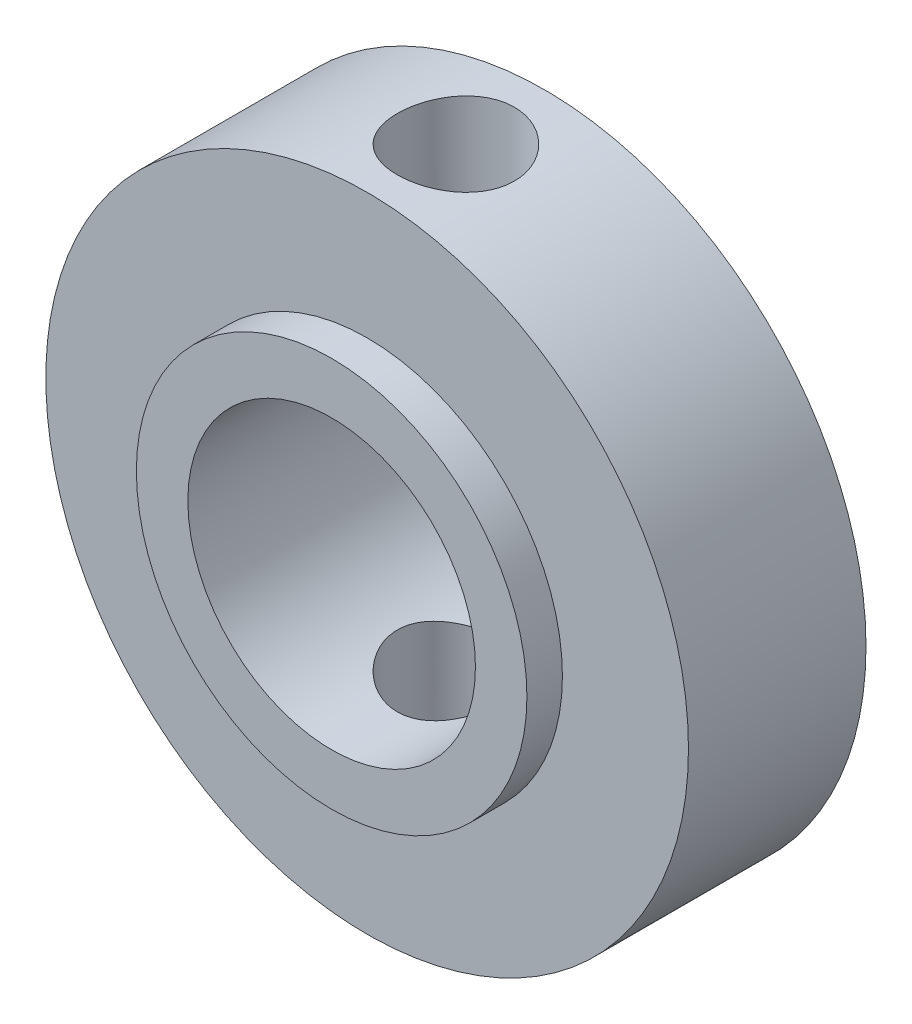
SolidWorks part; units mm, degrees
ref_plane "Plan de face" through (0, 0, 0) normal (0, 0, 1) x (1, 0, 0)
ref_plane "Plan de dessus" through (0, 0, 0) normal (0, 1, 0) x (1, 0, 0)
ref_plane "Plan de droite" through (0, 0, 0) normal (1, 0, 0) x (0, 0, -1)
sketch "Esquisse1" plane through (0, 0, 0) normal (0, 0, 1) x (1, 0, 0)
  circle A0 centre (0, 0) radius 4.05
  circle A1 centre (0, 0) radius 9.05
  dimension "D1" = 8.1
  dimension "D2" = 5
extrude "Boss.-Extru.1" add sketch "Esquisse1" along normal blind 5
sketch "Esquisse2" plane through (0, 0, 0) normal (0, 1, 0) x (1, 0, 0)
  line L0 (0, 0) -> (0, -5) construction
  line L1 (-9.05, -5) -> (9.05, -5) construction
  circle A0 centre (0, -2.5) radius 1.65
  dimension "D1" = 3.3
extrude "Enlèv. mat.-Extru.1" cut sketch "Esquisse2" against normal through all both and the other way through all
sketch "Esquisse3" plane through (0, 0, 5) normal (0, 0, 1) x (1, 0, 0)
  circle A0 centre (0, 0) radius 5.5
  circle A1 centre (0, 0) radius 4.05
  dimension "D1" = 8.1
  dimension "D2" = 11
extrude "Boss.-Extru.2" add sketch "Esquisse3" along normal blind 1
